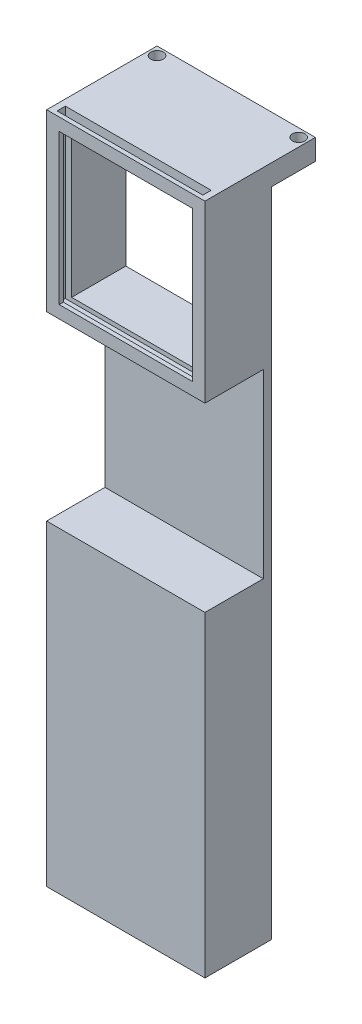
SolidWorks part; units mm, degrees
ref_plane "Přední rovina" through (0, 0, 0) normal (0, 0, 1) x (1, 0, 0)
ref_plane "Horní rovina" through (0, 0, 0) normal (0, 1, 0) x (1, 0, 0)
ref_plane "Pravá rovina" through (0, 0, 0) normal (1, 0, 0) x (0, 0, -1)
sketch "Skica2" plane through (0, 0, 0) normal (0, 0, 1) x (1, 0, 0)
  line L0 (36, -5) -> (-2, -5) construction
  line L2 (36, 151.5) -> (36, 114.5)
  line L3 (36, -5) -> (33, -5)
  line L4 (33, 151.5) -> (33, 117.5)
  line L5 (36, 151.5) -> (36, 156.5)
  line L7 (-2, 151.5) -> (-2, 114.5)
  line L8 (-2, -5) -> (1, -5)
  line L9 (1, 151.5) -> (1, 117.5)
  line L11 (36, 156.5) -> (-2, 156.5)
  line L13 (-2, 156.5) -> (-2, 151.5)
  line L14 (1, 151.5) -> (1, 153.5)
  line L15 (1, 153.5) -> (33, 153.5)
  line L16 (33, 153.5) -> (33, 151.5)
  line L17 (1, 68) -> (33, 68)
  line L19 (33, 71) -> (1, 71)
  line L21 (1, 117.5) -> (33, 117.5)
  line L23 (33, 114.5) -> (1, 114.5)
  line L25 (33, 151.5) -> (33, -1.2679) construction
  line L26 (1, 151.5) -> (1, -1.2679) construction
  line L27 (32.2679, -2) -> (1.7321, -2)
  line L28 (1, -5) -> (33, -5)
  line L29 (32.2679, -2) -> (1.7321, -2) construction
  line L30 (25.9, 63) -> (7.9, 63) construction
  line L31 (33.1, 151.5) -> (1.1, 151.5) construction
  line L32 (1, 114.5) -> (-2, 114.5)
  line L33 (1, 71) -> (-2, 71)
  line L34 (33, 114.5) -> (36, 114.5)
  line L35 (33, 71) -> (36, 71)
  line L36 (36, 71) -> (36, -5)
  line L37 (33, 68) -> (33, -1.2679)
  line L38 (1, 68) -> (1, -1.2679)
  line L39 (-2, 71) -> (-2, -5)
  arc A0 (1, -1.2679) -> (1.7321, -2) centre (0, -3) cw
  arc A2 (33, -1.2679) -> (32.2679, -2) centre (34, -3) ccw
  circle A4 centre (0, -3) radius 1.75
  circle A5 centre (34, -3) radius 1.75
  dimension "D11" = 3.5
  dimension "D1" = 5
  dimension "D2" = 3
  dimension "D3" = 42
  dimension "D4" = 3
  dimension "D5" = 43.5
  dimension "D6" = 2
  dimension "D7" = 3
  dimension "D8" = 3
  dimension "D9" = 3
  dimension "D10" = 3
extrude "Přidat vysunutím1" add sketch "Skica2" along normal up to vertex (12 mm away)
sketch "Skica3" plane through (0, 0, 0) normal (0, 0, 1) x (1, 0, 0)
  line L1 (-2, 114.5) -> (36, 114.5)
  line L2 (-2, 114.5) -> (-2, 71)
  line L3 (-2, 71) -> (36, 71)
  line L4 (36, 114.5) -> (36, 71)
extrude "Přidat vysunutím2" add sketch "Skica3" along normal blind 2
sketch "Skica4" plane through (0, 0, 0) normal (0, 0, -1) x (-1, 0, 0)
  line L0 (2, 156.5) -> (2, -5) construction
  line L1 (-36, 156.5) -> (2, 156.5)
  line L2 (-36, 156.5) -> (-36, 154.5)
  line L3 (-33, 153.5) -> (-1, 153.5)
  line L4 (2, 156.5) -> (2, 154.5)
  line L5 (-33, 117.5) -> (-33, 153.5) construction
  line L6 (-36, 151.5) -> (-33, 151.5)
  line L7 (-36, 151.5) -> (-36, 154.5)
  line L9 (-33, 151.5) -> (-33, 153.5)
  line L10 (-33, 153.5) -> (-1, 153.5) construction
  line L12 (2, 151.5) -> (-1, 151.5)
  line L13 (2, 151.5) -> (2, 154.5)
  line L15 (-1, 151.5) -> (-1, 153.5)
extrude "Přidat vysunutím3" add sketch "Skica4" along normal up to vertex (10.5 mm away)
sketch "Skica5" plane through (0, 0, -10.5) normal (0, 0, -1) x (-1, 0, 0)
  line L1 (-36, 151.5) -> (2, 151.5)
  line L2 (-36, 151.5) -> (-36, 156.5)
  line L3 (-36, 156.5) -> (2, 156.5)
  line L4 (2, 151.5) -> (2, 156.5)
extrude "Přidat vysunutím4" add sketch "Skica5" against normal blind 4
sketch "Skica6" plane through (0, 156.5, 0) normal (0, 1, 0) x (1, 0, 0)
  circle A0 centre (34, 8.5) radius 1.5
  circle A1 centre (0, 8.5) radius 1.5
  circle A2 centre (0, 8.5) radius 1.75 construction
  circle A3 centre (34, 8.5) radius 1.75 construction
  dimension "D1" = 3
sketch "Skica7" plane through (0, 0, 12) normal (0, 0, 1) x (1, 0, 0)
  line L1 (-2, 71) -> (36, 71)
  line L2 (-2, 71) -> (-2, -5)
  line L3 (-2, -5) -> (36, -5)
  line L4 (36, 71) -> (36, -5)
extrude "Přidat vysunutím5" add sketch "Skica7" along normal blind 4
sketch "Skica8" plane through (0, 0, 12) normal (0, 0, 1) x (1, 0, 0)
  line L1 (36, 156.5) -> (-2, 156.5)
  line L2 (36, 156.5) -> (36, 114.5)
  line L3 (36, 114.5) -> (-2, 114.5)
  line L4 (-2, 156.5) -> (-2, 114.5)
  line L5 (1, 153.5) -> (33, 153.5)
  line L6 (1, 153.5) -> (1, 117.5)
  line L7 (1, 117.5) -> (33, 117.5)
  line L8 (33, 153.5) -> (33, 117.5)
extrude "Přidat vysunutím6" add sketch "Skica8" along normal blind 4
sketch "Skica9" plane through (0, 156.5, 0) normal (0, 1, 0) x (1, 0, 0)
  line L0 (36, -16) -> (-2, -16) construction
  line L1 (34.5, -15) -> (-0.5, -15)
  line L2 (34.5, -15) -> (34.5, -13)
  line L3 (34.5, -13) -> (-0.5, -13)
  line L4 (-0.5, -15) -> (-0.5, -13)
  line L5 (36, -16) -> (36, 10.5) construction
  line L6 (-2, -16) -> (-2, 10.5) construction
  dimension "D1" = 2
  dimension "D2" = 1
  dimension "D3" = 1.5
  dimension "D4" = 1.5
  dimension "D5" = 35
extrude "Odebrat vysunutím2" cut sketch "Skica9" against normal blind 40
sketch "Skica11" plane through (0, 156.5, 0) normal (0, 1, 0) x (1, 0, 0)
  circle A0 centre (0, 8.5) radius 1.5
  circle A1 centre (34, 8.5) radius 1.5
  circle A2 centre (34, 8.5) radius 1.75 construction
  circle A3 centre (0, 8.5) radius 1.75 construction
  dimension "D1" = 3
extrude "Odebrat vysunutím3" cut sketch "Skica11" against normal up to vertex
sketch "Skica13" plane through (0, 0, 16) normal (0, 0, 1) x (1, 0, 0)
  circle A0 centre (0, -3) radius 1.75
  circle A1 centre (34, -3) radius 1.75
  circle A2 centre (34, -3) radius 1.75 construction
  circle A3 centre (0, -3) radius 1.75 construction
  circle A4 centre (34, -3) radius 1.5 construction
extrude "Přidat vysunutím7" add sketch "Skica13" against normal blind 12
